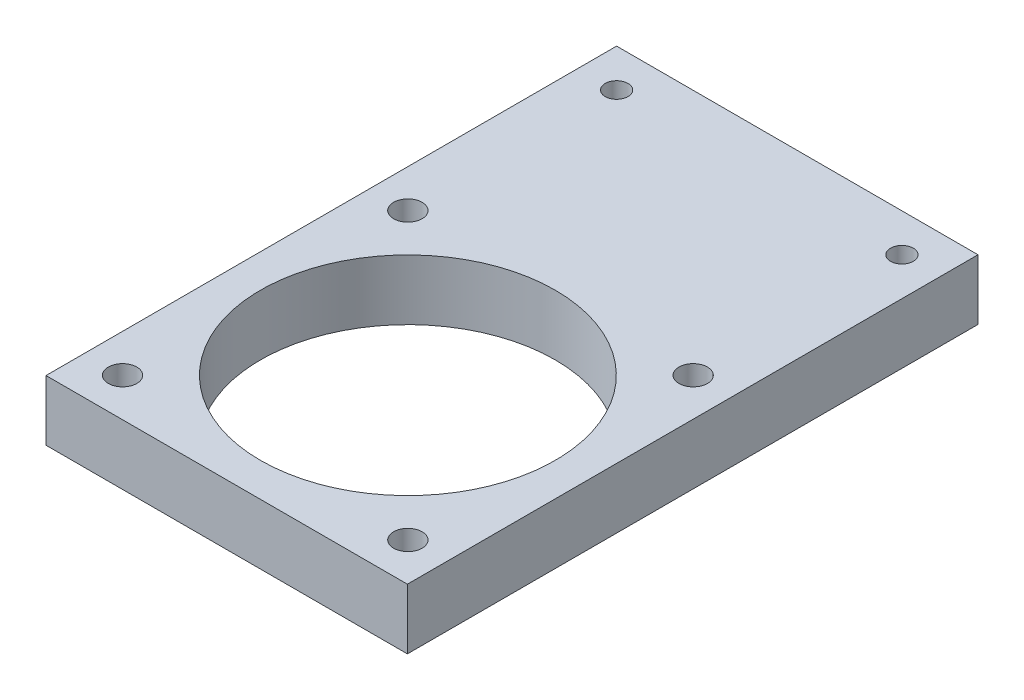
SolidWorks part; units mm, degrees
ref_plane "Front Plane" through (0, 0, 0) normal (0, 0, 1) x (1, 0, 0)
ref_plane "Top Plane" through (0, 0, 0) normal (0, 1, 0) x (1, 0, 0)
ref_plane "Right Plane" through (0, 0, 0) normal (1, 0, 0) x (0, 0, -1)
sketch "Sketch1" plane through (0, 0, 0) normal (0, 1, 0) x (1, 0, 0)
  line L0 (4, 4.05) -> (34, 4.05) construction
  line L1 (0, 0) -> (38, 0)
  line L4 (38, 0) -> (38, 60)
  line L5 (4, 34.05) -> (4, 4.05) construction
  line L7 (0, 0) -> (0, 60)
  line L9 (0, 60) -> (38, 60)
  circle A0 centre (4, 4.05) radius 1.5
  circle A1 centre (34, 4.05) radius 1.5
  circle A2 centre (34, 34.05) radius 1.5
  circle A3 centre (4, 34.05) radius 1.5
  circle A4 centre (19, 19.05) radius 15.5
  circle A7 centre (4, 56) radius 1.2
  circle A8 centre (34, 56) radius 1.2
  point P7 (19, 4.05)
  point P8 (0, 19.05)
  point P16 (19, 0)
  point P18 (4, 19.05)
  point P20 (0, 0)
  point P23 (0, 0)
  point P24 (0, 0)
  dimension "D5" = 3
  dimension "D8" = 31
  dimension "D9" = 2.4
  dimension "D12" = 2.4
  dimension "D6" = 30
  dimension "D7" = 30
  dimension "D2" = 19.05
  dimension "D10" = 38
  dimension "D11" = 60
  dimension "D13" = 4
  dimension "D3" = 2
  dimension "D4" = 2
extrude "Boss-Extrude1" add sketch "Sketch1" along normal blind 6.35
equation "\"D12@Sketch1\"=\"D9@Sketch1\""
